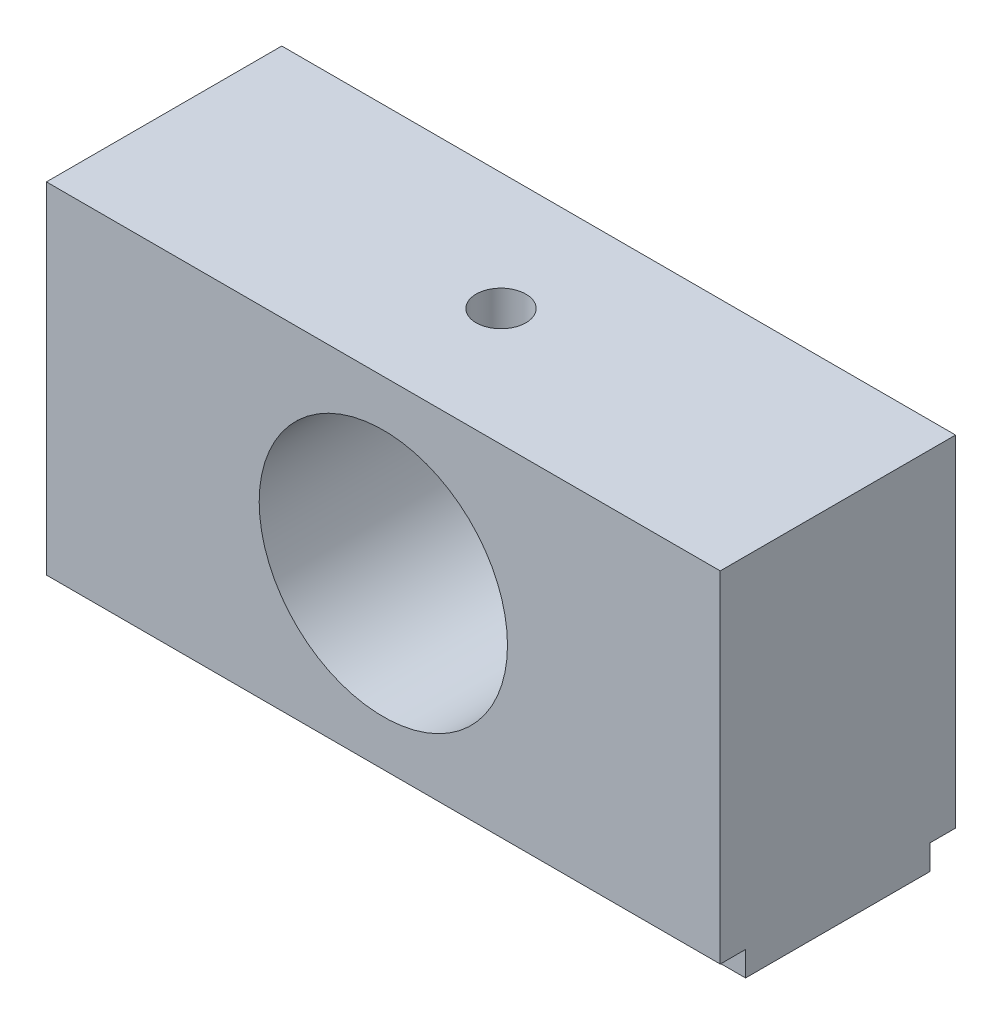
SolidWorks part; units mm, degrees
ref_plane "Front" through (0, 0, 0) normal (0, 0, 1) x (1, 0, 0)
ref_plane "Top" through (0, 0, 0) normal (0, 1, 0) x (1, 0, 0)
ref_plane "Right" through (0, 0, 0) normal (1, 0, 0) x (0, 0, -1)
sketch "Sketch1" plane through (0, 0, 0) normal (0, 0, 1) x (1, 0, 0)
  line L1 (-16.1377, 27.8174) -> (52.9503, 27.8174)
  line L2 (-16.1377, 27.8174) -> (-16.1377, -9.6326)
  line L3 (-16.1377, -9.6326) -> (52.9503, -9.6326)
  line L4 (52.9503, 27.8174) -> (52.9503, -9.6326)
extrude "Extrude1" add sketch "Sketch1" along normal blind 24.13
sketch "Sketch2" plane through (-16.1377, 0, 0) normal (-1, 0, 0) x (0, 0, 1)
  line L0 (-1.3944, -7.2196) -> (2.5972, -7.2196)
  line L1 (2.5972, -7.2196) -> (2.5972, -10.3701)
  line L2 (2.5972, -10.3701) -> (21.5328, -10.3701)
  line L3 (21.5328, -10.3701) -> (21.5328, -7.2196)
  line L4 (21.5328, -7.2196) -> (26.0242, -7.2196)
  line L5 (0, 27.8174) -> (0, -9.6326) construction
  line L6 (24.13, 27.8174) -> (24.13, -9.6326) construction
  arc A0 (-1.3944, -7.2196) -> (26.0242, -7.2196) centre (12.3149, -5.4294) ccw
extrude "Cut-Extrude1" cut sketch "Sketch2" against normal blind 83.312 and the other way blind 8.128
sketch "Sketch3" plane through (-16.1377, 0, 0) normal (-1, 0, 0) x (0, 0, 1)
  line L0 (24.13, 27.8174) -> (24.13, -7.2196) construction
  line L1 (24.13, 27.8174) -> (0, 27.8174) construction
  point P0 (11.43, 10.6089)
hole_wizard "1/4-20 Tapped Hole1"
sketch3d "3DSketch1"
  point P0 (-16.1377, 5.6709, 11.43)
cosmetic thread "Cosmetic Thread1" [suppressed]
sketch "Sketch4" plane through (-16.1377, 5.6709, 11.43) normal (0, 1, 0) x (0, 0, 1)
  line L0 (0, 0) -> (0, 18.0438)
  line L1 (0, 18.0438) -> (2.5527, 16.51)
  line L2 (2.5527, 16.51) -> (2.5527, 0)
  line L5 (2.5527, 0) -> (0, 0)
  line L10 (0, 18.0438) -> (-2.5527, 16.51) construction
  line L11 (0, -6.35) -> (0, 107.95) construction
sketch "Sketch5" plane through (0, -9.6326, 0) normal (0, -1, 0) x (1, 0, 0)
  line L0 (-16.1377, 21.5328) -> (-16.1377, 2.5971) construction
  line L2 (18.4063, 24.13) -> (18.4063, 0) construction
  line L3 (52.9503, 24.13) -> (-16.1377, 24.13) construction
  line L4 (52.9503, 0) -> (-16.1377, 0) construction
  line L5 (52.9503, 21.5328) -> (52.9503, 2.5972) construction
  point P0 (-2.8154, 11.6021)
  point P1 (39.628, 3.5235)
sketch "Sketch9" plane through (0, 27.8174, 0) normal (0, 1, 0) x (-1, 0, 0)
  line L0 (-18.4063, 0) -> (-18.4063, 24.13) construction
  line L1 (-52.9503, 0) -> (16.1377, 0) construction
  line L2 (-52.9503, 24.13) -> (16.1377, 24.13) construction
  line L3 (16.1377, 12.065) -> (-52.9503, 12.065) construction
  line L4 (16.1377, 24.13) -> (16.1377, 0) construction
  line L5 (-52.9503, 24.13) -> (-52.9503, 0) construction
  line L6 (-15.834, 7.62) -> (-20.8386, 7.62) construction
  line L7 (-15.834, 16.51) -> (-20.8386, 16.51) construction
  text T0 "0" font "Century Gothic" height in points 32
sketch "Sketch11" plane through (-16.1377, 0, 0) normal (-1, 0, 0) x (0, 0, 1)
  line L0 (12.065, -9.6326) -> (12.0774, 22.8794) construction
  line L1 (21.5328, -9.6326) -> (2.5971, -9.6326) construction
  line L2 (0, -7.2196) -> (2.5972, -7.2196) construction
  line L3 (-4.9594, -7.0896) -> (2.5971, -7.0896)
  line L4 (-4.9594, -7.0896) -> (-4.9594, -9.6326)
  line L5 (-4.9594, -9.6326) -> (2.5971, -9.6326)
  line L6 (2.5971, -7.0896) -> (2.5971, -9.6326)
  line L7 (21.5348, -7.0968) -> (21.5328, -9.6398)
  line L8 (29.0894, -9.6456) -> (21.5328, -9.6398)
  line L9 (29.0913, -7.1026) -> (29.0894, -9.6456)
  line L10 (29.0913, -7.1026) -> (21.5348, -7.0968)
  point P9 (1.2986, -7.2196)
extrude "Cut-Extrude4" cut sketch "Sketch11" along normal blind 25.4 and the other way blind 89.662
sketch "Sketch13" plane through (0, -9.6326, 0) normal (0, -1, 0) x (1, 0, 0)
  line L0 (52.9503, 12.065) -> (-16.1377, 12.065) construction
  line L1 (52.9503, 21.5328) -> (52.9503, 2.5972) construction
  line L2 (-16.1377, 21.5328) -> (-16.1377, 2.5971) construction
  point P6 (-3.1837, 12.065)
  point P7 (39.9963, 12.065)
hole_wizard "5/16-24 Tapped Hole1" positions "3DSketch2" profile "Sketch14"
sketch3d "3DSketch2"
  point P0 (-3.1837, -9.6326, 12.065)
  point P2 (39.9963, -9.6326, 12.065)
sketch "Sketch14" plane through (-3.1837, -9.6326, 12.065) normal (1, 0, 0) x (0, 0, -1)
  line L0 (0, 0) -> (0, 21.1282)
  line L1 (0, 21.1282) -> (3.4544, 19.0525)
  line L2 (3.4544, 19.0525) -> (3.4544, 0)
  line L5 (3.4544, 0) -> (0, 0)
  line L10 (0, 21.1282) -> (-3.4544, 19.0525) construction
  line L11 (0, -6.35) -> (0, 107.95) construction
cosmetic thread "Cosmetic Thread9"
cosmetic thread "Cosmetic Thread10"
sketch "Sketch15" plane through (0, 0, 0) normal (0, 0, 1) x (1, 0, 0)
  line L0 (52.9503, 27.8174) -> (-16.1377, 27.8174) construction
  circle A0 centre (18.4063, 10.3174) radius 12.73
  point P0 (-16.1377, 27.8174)
  point P1 (52.9503, 27.8174)
  point P2 (18.4063, 23.0474)
extrude "Cut-Extrude5" cut sketch "Sketch15" against normal blind 11.938 and the other way blind 38.608
ref_plane "Plane1" through (0, 0, 4.73) normal (0, 0, 1) x (1, 0, 0)
sketch "Sketch16" plane through (0, 0, 4.73) normal (0, 0, 1) x (1, 0, 0)
  circle A0 centre (18.4063, 10.3174) radius 9.7
  circle A1 centre (18.4063, 10.3174) radius 14.7
extrude "Boss-Extrude1" add sketch "Sketch16" against normal up to vertex (4.73 mm away)
sketch "Sketch17" plane through (0, 27.8174, 0) normal (0, 1, 0) x (-1, 0, 0)
  point P0 (-18.4063, 12.065)
hole_wizard "1/4-20 Tapped Hole2" positions "3DSketch3" profile "Sketch18"
sketch3d "3DSketch3"
  point P0 (18.4063, 27.8174, 12.065)
sketch "Sketch18" plane through (18.4063, 27.8174, 12.065) normal (1, 0, 0) x (0, 0, 1)
  line L0 (0, 0) -> (0, 18.0438)
  line L1 (0, 18.0438) -> (2.5527, 16.51)
  line L2 (2.5527, 16.51) -> (2.5527, 0)
  line L5 (2.5527, 0) -> (0, 0)
  line L10 (0, 18.0438) -> (-2.5527, 16.51) construction
  line L11 (0, -6.35) -> (0, 107.95) construction
cosmetic thread "Hole Thread1"
